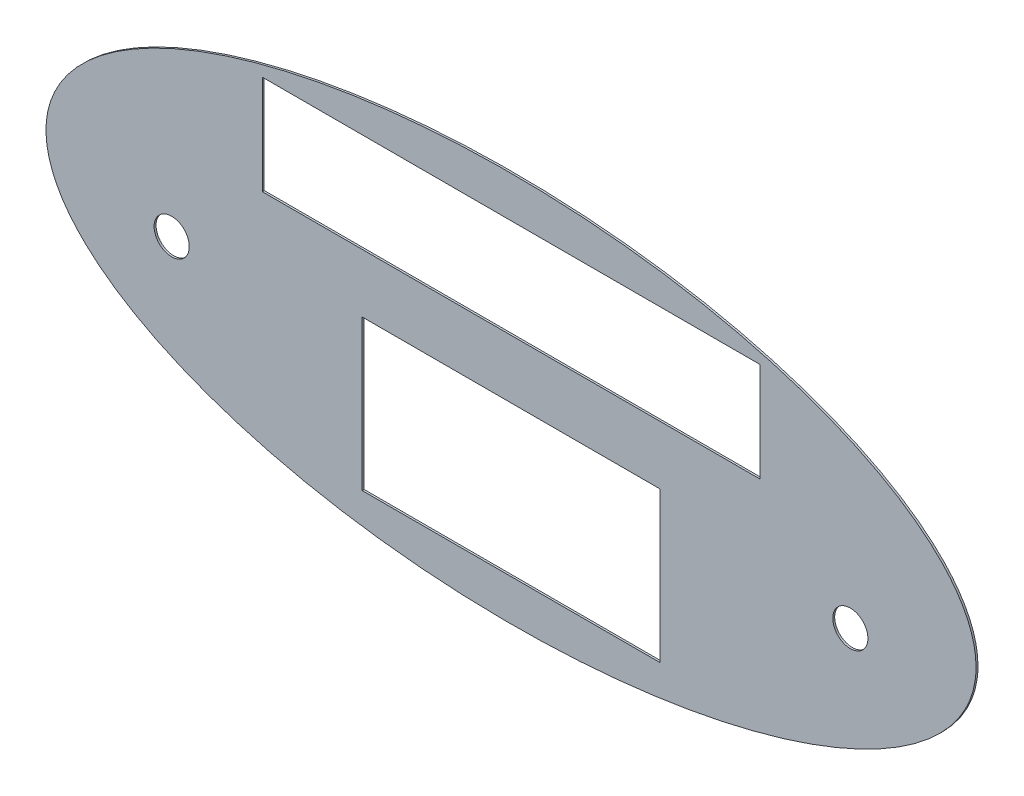
SolidWorks part; units mm, degrees
material "Balsa"
ref_plane "Front Plane" through (0, 0, 0) normal (0, 0, 1) x (1, 0, 0)
ref_plane "Top Plane" through (0, 0, 0) normal (0, 1, 0) x (1, 0, 0)
ref_plane "Right Plane" through (0, 0, 0) normal (1, 0, 0) x (0, 0, -1)
sketch "fuselage_front" plane through (0, 0, 0) normal (0, 0, 1) x (1, 0, 0)
  line L0 (0, -77) -> (0, 0) construction
  line L1 (-127.4, 80.8) -> (127.4, 80.8)
  line L2 (-127.4, 80.8) -> (-127.4, 30)
  line L3 (-127.4, 30) -> (127.4, 30)
  line L4 (127.4, 80.8) -> (127.4, 30)
  line L5 (-76.2, 0) -> (76.2, 0)
  line L6 (-76.2, 0) -> (-76.2, -77)
  line L7 (-76.2, -77) -> (76.2, -77)
  line L8 (76.2, 0) -> (76.2, -77)
  line L9 (0, 80.8) -> (0, 30) construction
  line L10 (-76.2, -38.5) -> (76.2, -38.5) construction
  line L11 (238.1768, 1.9) -> (-238.1768, 1.9) construction
  circle A2 centre (173.785, -13.1) radius 9
  circle A3 centre (-173.785, -13.1) radius 9
  ellipse E0 centre (0, 1.9) end of major axis (238.1768, 1.9) minor radius 100
  dimension "D1" = 18
  dimension "D3" = 15
  dimension "PAX_Height" = 50.8
  dimension "D2" = 173.785
  dimension "PAX_Width" = 254.8
  dimension "Cargo_Height" = 77
  dimension "Cargo_Width" = 152.4
  dimension "PAX_Cargo_Spacing_Y" = 30
  dimension "Ellipse_Semi_Minor" = 100
  dimension "Ellipse_Semi_Major" = 238.1768
  dimension "Ellipse_Centre_Y" = 78.9
extrude "fuselage_front_plate" add sketch "fuselage_front" along normal blind 1
